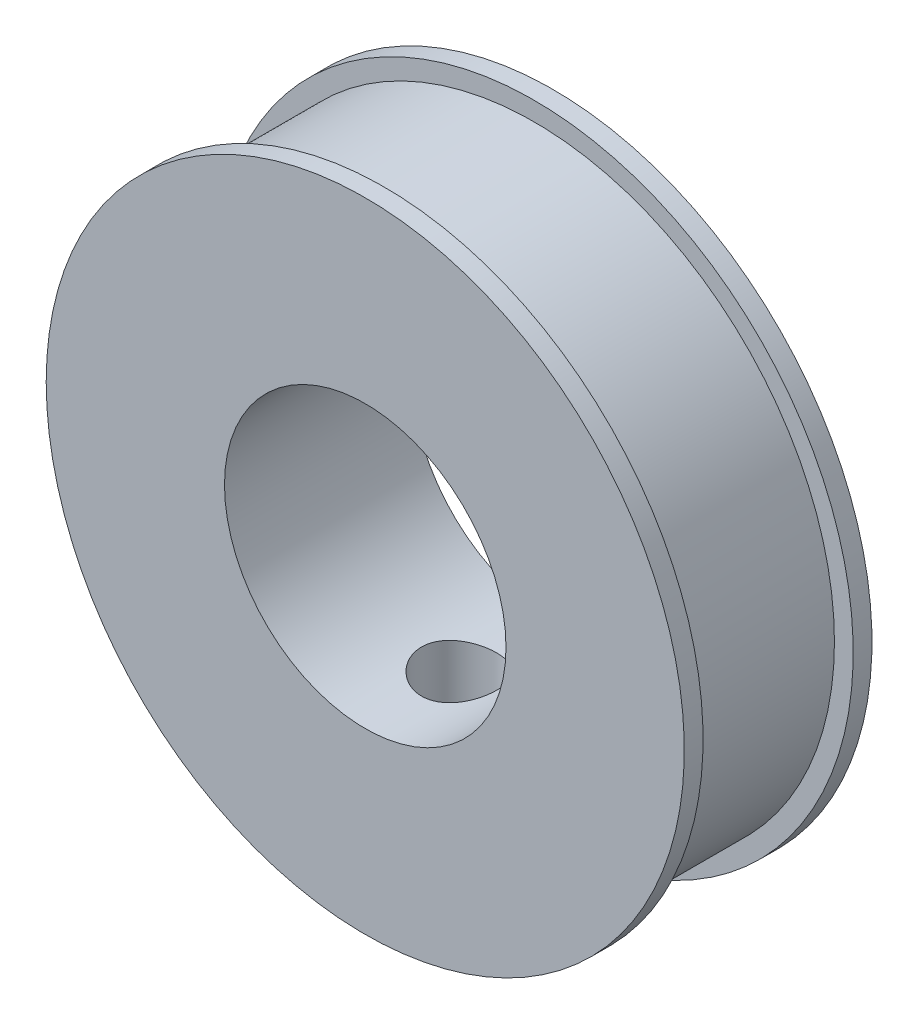
SolidWorks part; units mm, degrees
ref_plane "Front Plane" through (0, 0, 0) normal (0, 0, 1) x (1, 0, 0)
ref_plane "Top Plane" through (0, 0, 0) normal (0, 1, 0) x (1, 0, 0)
ref_plane "Right Plane" through (0, 0, 0) normal (1, 0, 0) x (0, 0, -1)
sketch "Sketch1" plane through (0, 0, 0) normal (0, 1, 0) x (1, 0, 0)
  line L0 (0, 0) -> (17, 0)
  line L1 (17, 0) -> (17, 1)
  line L2 (17, 1) -> (16, 1)
  line L3 (16, 1) -> (16, 9)
  line L4 (16, 9) -> (17, 9)
  line L5 (17, 9) -> (17, 10)
  line L6 (17, 10) -> (0, 10)
  line L7 (0, 10) -> (0, 0)
  dimension "D1" = 1
  dimension "D2" = 1
  dimension "D3" = 8
  dimension "D4" = 17
  dimension "D5" = 1
revolve "Revolve1" add sketch "Sketch1" angle 360 about L7
sketch "Sketch2" plane through (0, 0, -10) normal (0, 0, -1) x (-1, 0, 0)
  circle A0 centre (0, 0) radius 7.5
  dimension "D1" = 15
extrude "Cut-Extrude1" cut sketch "Sketch2" against normal through all
sketch "Sketch3" plane through (0, 0, 0) normal (0, 1, 0) x (1, 0, 0)
  line L0 (0, 5) -> (0, 9) construction
  line L1 (-16, 9) -> (16, 9) construction
  circle A0 centre (0, 5) radius 2
  dimension "D1" = 4
  dimension "D2" = 4
extrude "Cut-Extrude2" cut sketch "Sketch3" against normal blind 27
